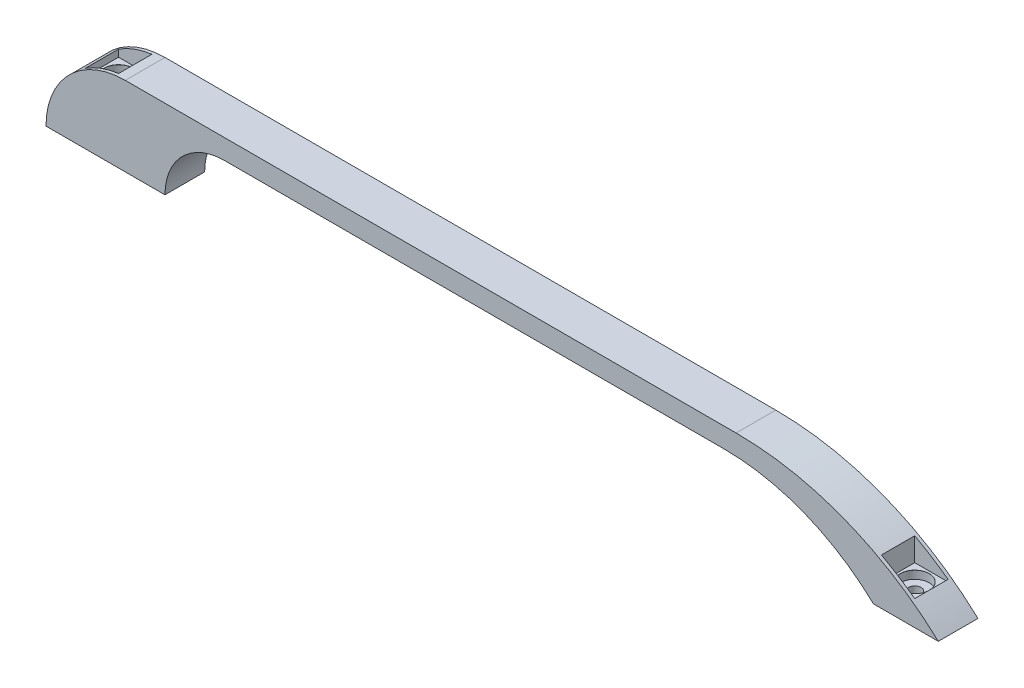
SolidWorks part; units mm, degrees
material "3.3315 (EN-AW 5005)"
ref_plane "Płaszczyzna przednia" through (0, 0, 0) normal (0, 0, 1) x (1, 0, 0)
ref_plane "Płaszczyzna górna" through (0, 0, 0) normal (0, 1, 0) x (1, 0, 0)
ref_plane "Płaszczyzna prawa" through (0, 0, 0) normal (1, 0, 0) x (0, 0, -1)
sketch "Szkic1" plane through (0, 0, 0) normal (0, 0, 1) x (1, 0, 0)
  line L1 (40, 40) -> (348.0196, 40)
  line L7 (0, 0) -> (17.8994, 0) construction
  line L10 (450, 0) -> (417.2807, 0)
  line L11 (0, 0) -> (60, 0)
  line L12 (342, 30) -> (116.3082, 30)
  line L13 (90, 30) -> (116.3082, 30)
  arc A1 (348.0196, 40) -> (450, 0) centre (348.0196, -110) cw
  arc A5 (342, 30) -> (417.2807, 0) centre (341.7821, -79.9998) cw
  arc A6 (60, 0) -> (90, 30) centre (90, 0) cw
  arc A7 (40, 40) -> (0, 0) centre (40, 0) ccw
  dimension "D3" = 60
  dimension "D5" = 150
  dimension "D6" = 110
  dimension "D8" = 30
  dimension "D9" = 40
  dimension "D1" = 450
  dimension "D2" = 40
  dimension "D4" = 252
  dimension "D7" = 32.7193
  dimension "D10" = 225.6918
extrude "Dodanie-wyciągnięcie2" add sketch "Szkic1" along normal blind 20
ref_plane "Płaszczyzna1" through (0, 30, 0) normal (0, 1, 0) x (1, 0, 0)
sketch "Szkic28" plane through (0, 30, 0) normal (0, 1, 0) x (1, 0, 0)
  line L0 (18.2, -1.6) -> (18.2, -18.4)
  line L1 (18.2, -18.4) -> (35, -18.4)
  line L2 (35, -18.4) -> (35, -1.6)
  line L3 (35, -1.6) -> (18.2, -1.6)
  line L4 (40, 0) -> (0, 0) construction
  line L5 (0, -20) -> (40, -20) construction
  line L8 (40, -20) -> (40, 0) construction
  dimension "D1" = 1.6
  dimension "D2" = 1.6
  dimension "D3" = 5
extrude "Wytnij-wyciągnięcie1" cut sketch "Szkic28" along normal blind 20
ref_plane "Płaszczyzna2" through (0, 10, 0) normal (0, 1, 0) x (1, 0, 0)
sketch "Szkic29" plane through (0, 10, 0) normal (0, 1, 0) x (1, 0, 0)
  line L0 (419.7, -18.4) -> (436.5, -18.4)
  line L1 (436.5, -18.4) -> (436.5, -1.6)
  line L2 (436.5, -1.6) -> (419.7, -1.6)
  line L3 (419.7, -1.6) -> (419.7, -18.4)
  line L4 (450, 0) -> (348.0196, 0) construction
  line L5 (348.0196, -20) -> (450, -20) construction
  line L6 (450, -20) -> (450, 0) construction
  dimension "D1" = 16.8
  dimension "D2" = 16.8
  dimension "D3" = 1.6
  dimension "D4" = 1.6
  dimension "D5" = 13.5
extrude "Wytnij-wyciągnięcie2" cut sketch "Szkic29" along normal blind 20
sketch "Szkic30" plane through (0, 30, 0) normal (0, 1, 0) x (1, 0, 0)
  line L0 (18.2, -10) -> (35, -10) construction
  line L1 (18.2, -1.6) -> (18.2, -18.4) construction
  line L2 (35, -18.4) -> (35, -1.6) construction
  line L3 (26.6, -1.6) -> (26.6, -18.4) construction
  line L4 (35, -1.6) -> (18.2, -1.6) construction
  line L5 (35, -18.4) -> (18.2, -18.4) construction
sketch "Szkic31" plane through (0, 10, 0) normal (0, 1, 0) x (1, 0, 0)
  line L0 (419.7, -10) -> (436.5, -10) construction
  line L1 (428.1, -1.6) -> (428.1, -18.4) construction
  line L2 (436.5, -1.6) -> (419.7, -1.6) construction
  line L3 (419.7, -1.6) -> (419.7, -18.4) construction
  point P11 (428.1, -10)
hole_wizard "Pogłębienie walcowe pod M6 wkręt z łbem sześciokątnym1" positions "Szkic31" profile "Szkic32" counterbore size "M6" standard "ISO"
sketch "Szkic32" plane through (428.1, 10, 10) normal (1, 0, 0) x (0, 0, 1)
  line L0 (0, 0) -> (0, 26.9228)
  line L1 (0, 26.9228) -> (3.2, 25)
  line L2 (3.2, 25) -> (3.2, 4)
  line L3 (3.2, 4) -> (7.2735, 4)
  line L5 (7.2735, 4) -> (7.2735, 0.025)
  line L6 (7.2735, 0.025) -> (7.2985, 0)
  line L7 (7.2985, 0) -> (0, 0)
  line L8 (-7.2735, 0.025) -> (-7.2985, 0) construction
  line L10 (0, 26.9228) -> (-3.2, 25) construction
  line L11 (0, -6.35) -> (0, 107.95) construction
  dimension "Średnica otworu" = 6.4
  dimension "Głębokość otworu" = 25
  dimension "Średnica pogłębienia walcowego" = 14.547
  dimension "Głębokość pogłębienia walcowego" = 4
  dimension "Średnica zewnętrznego pogłębienia stożkowego" = 14.597
  dimension "Kąt zewnętrznego pogłębienia stożkowego" = 90
  dimension "Kąt wiertła" = 118
hole_wizard "Pogłębienie walcowe pod M6 wkręt z łbem sześciokątnym2" positions "Szkic33" profile "Szkic34" counterbore size "M6" standard "ISO"
sketch "Szkic33" plane through (0, 30, 0) normal (0, 1, 0) x (1, 0, 0)
  line L0 (26.6, -1.6) -> (26.6, -18.4) construction
  point P0 (26.6, -10)
sketch "Szkic34" plane through (26.6, 30, 10) normal (1, 0, 0) x (0, 0, 1)
  line L0 (0, 0) -> (0, 41.9228)
  line L1 (0, 41.9228) -> (3.2, 40)
  line L2 (3.2, 40) -> (3.2, 4)
  line L3 (3.2, 4) -> (7.2735, 4)
  line L5 (7.2735, 4) -> (7.2735, 0.025)
  line L6 (7.2735, 0.025) -> (7.2985, 0)
  line L7 (7.2985, 0) -> (0, 0)
  line L8 (-7.2735, 0.025) -> (-7.2985, 0) construction
  line L10 (0, 41.9228) -> (-3.2, 40) construction
  line L11 (0, -6.35) -> (0, 107.95) construction
  dimension "Średnica otworu" = 6.4
  dimension "Głębokość otworu" = 40
  dimension "Średnica pogłębienia walcowego" = 14.547
  dimension "Głębokość pogłębienia walcowego" = 4
  dimension "Średnica zewnętrznego pogłębienia stożkowego" = 14.597
  dimension "Kąt zewnętrznego pogłębienia stożkowego" = 90
  dimension "Kąt wiertła" = 118
sketch "Szkic35" plane through (0, 0, 0) normal (0, 1, 0) x (1, 0, 0)
  line L0 (29.8, -10) -> (424.9, -10) construction
  circle A0 centre (26.6, -10) radius 3.2 construction
  circle A1 centre (428.1, -10) radius 3.2 construction
  dimension "D1" = 395.1
sketch "Szkic36" plane through (0, 30, 0) normal (0, 1, 0) x (1, 0, 0)
  line L0 (26.6, -10) -> (428.1, -10) construction
  line L1 (18.2, -10) -> (35, -10) construction
  dimension "D1" = 401.5
